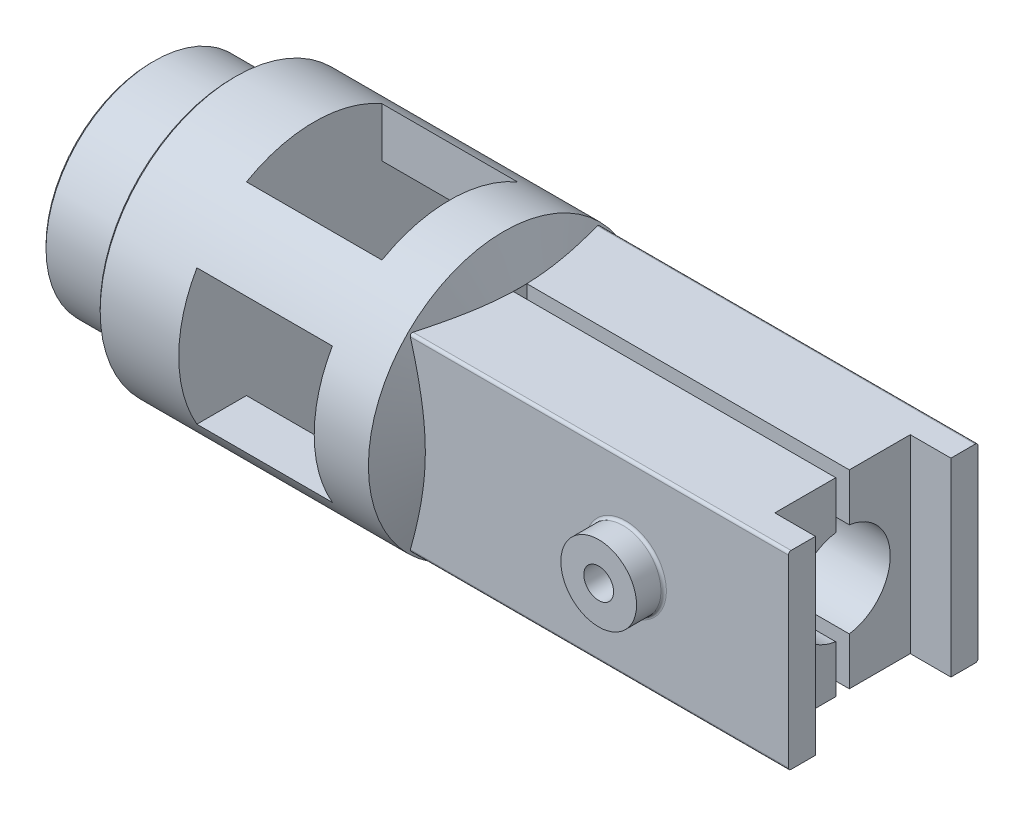
SolidWorks part; units mm, degrees
ref_plane "前视基准面" through (0, 0, 0) normal (0, 0, 1) x (1, 0, 0)
ref_plane "上视基准面" through (0, 0, 0) normal (0, 1, 0) x (1, 0, 0)
ref_plane "右视基准面" through (0, 0, 0) normal (1, 0, 0) x (0, 0, -1)
sketch "草图1" plane through (0, 0, 0) normal (0, 0, 1) x (1, 0, 0)
  line L0 (13, 0) -> (15, 0)
  line L1 (0, 0) -> (3, 0)
  line L2 (0, 0) -> (0, 4)
  line L3 (0, 4) -> (3, 4)
  line L4 (3, 0) -> (3, 4)
  line L5 (15, 0) -> (13, 5)
  line L6 (3, 0) -> (13, 0)
  line L7 (3, 0) -> (3, 5)
  line L8 (3, 5) -> (13, 5)
  line L9 (13, 0) -> (13, 5)
  point P8 (14.5028, 0)
  dimension "D1" = 4
  dimension "D2" = 5
  dimension "D3" = 3
  dimension "D4" = 13
  dimension "D5" = 15
revolve "旋转1" add sketch "草图1" angle 360 about L6
ref_plane "基准面1" through (6, 0, 0) normal (-1, 0, 0) x (0, 0, 1)
sketch "草图2" plane through (6, 0, 0) normal (-1, 0, 0) x (0, 0, 1)
  line L1 (-11.3913, 2.5) -> (11.3913, 2.5)
  line L2 (-11.3913, 2.5) -> (-11.3913, -2.5)
  line L3 (-11.3913, -2.5) -> (11.3913, -2.5)
  line L4 (11.3913, 2.5) -> (11.3913, -2.5)
  line L5 (-11.3913, 2.5) -> (11.3913, -2.5) construction
  line L6 (-11.3913, -2.5) -> (11.3913, 2.5) construction
  line L7 (-2.5, 14.208) -> (2.5, 14.208)
  line L8 (-2.5, 14.208) -> (-2.5, -14.208)
  line L9 (-2.5, -14.208) -> (2.5, -14.208)
  line L10 (2.5, 14.208) -> (2.5, -14.208)
  line L11 (-2.5, 14.208) -> (2.5, -14.208) construction
  line L12 (-2.5, -14.208) -> (2.5, 14.208) construction
  point P0 (0, 0)
  point P5 (0, 0)
  point P11 (-0.208, -1.7466)
  point P12 (0, 0)
  dimension "D1" = 5
extrude "切除-拉伸1" cut sketch "草图2" against normal blind 5 contours L1 L10 L3 L4 | L10 L3 L8 L9 | L10 L7 L8 L1 | L8 L1 L2 L3 | L10 L1 L8 L3
ref_plane "基准面2" through (27, 0, 0) normal (-1, 0, 0) x (0, 0, 1)
sketch "草图3" plane through (27, 0, 0) normal (-1, 0, 0) x (0, 0, 1)
  line L1 (-3.5, -3.5) -> (3.5, -3.5)
  line L2 (-3.5, -3.5) -> (-3.5, 3.5)
  line L3 (-3.5, 3.5) -> (3.5, 3.5)
  line L4 (3.5, -3.5) -> (3.5, 3.5)
  line L5 (-3.5, -3.5) -> (3.5, 3.5) construction
  line L6 (-3.5, 3.5) -> (3.5, -3.5) construction
  point P0 (0, 0)
  dimension "D1" = 7
extrude "凸台-拉伸1" add sketch "草图3" along normal up to next
sketch "草图4" plane through (27, 0, 0) normal (1, 0, 0) x (0, 0, -1)
  line L0 (-3.5, 3.5) -> (3.5, 3.5) construction
  line L1 (2.5, -3.5) -> (-2.5, -3.5)
  line L2 (2.5, -3.5) -> (2.5, 3.5)
  line L3 (2.5, 3.5) -> (-2.5, 3.5)
  line L4 (-2.5, -3.5) -> (-2.5, 3.5)
  line L5 (2.5, -3.5) -> (-2.5, 3.5) construction
  line L6 (2.5, 3.5) -> (-2.5, -3.5) construction
  point P0 (0, 0)
  dimension "D1" = 5
extrude "切除-拉伸2" cut sketch "草图4" against normal blind 1.5 contours L2 L1 L4 L3
sketch "草图5" plane through (25.5, 0, 0) normal (1, 0, 0) x (0, 0, -1)
  line L0 (2.5, -3.5) -> (-2.5, -3.5) construction
  line L1 (0.25, 3.5) -> (-0.25, 3.5)
  line L2 (0.25, 3.5) -> (0.25, -3.5)
  line L3 (0.25, -3.5) -> (-0.25, -3.5)
  line L4 (-0.25, 3.5) -> (-0.25, -3.5)
  line L5 (0.25, 3.5) -> (-0.25, -3.5) construction
  line L6 (0.25, -3.5) -> (-0.25, 3.5) construction
  circle A0 centre (0, 0) radius 1.7614
  dimension "4" = 3.5228
extrude "切除-拉伸3" cut sketch "草图5" against normal up to vertex (11.9 mm away) contours L4 A0 | L2 A0
sketch "草图6" plane through (0, 0, 3.5) normal (0, 0, 1) x (1, 0, 0)
  line L0 (27, -3.5) -> (27, 3.5) construction
  circle A0 centre (21, 0) radius 1.3966
  dimension "D1" = 6
extrude "凸台-拉伸2" add sketch "草图6" along normal blind 1
sketch "草图7" plane through (0, 0, 4.5) normal (0, 0, 1) x (1, 0, 0)
  circle A0 centre (21, 0) radius 0.55
  dimension "D1" = 1.1
extrude "切除-拉伸4" cut sketch "草图7" against normal through all
chamfer "倒角1" distance 0.5 angle 45 1 edges at (21.55, 0, -3.5)
fillet "圆角1" radius 0.1 1 edges at (19.6034, 0, 3.5)
chamfer "倒角2" distance 0.1 angle 45 2 edges at (3, 0, 5) (0, 0, 4)
fillet "圆角2" radius 0.1 4 edges at (20.0101, -3.5, -3.5) (20.0101, 3.5, -3.5) (20.0101, 3.5, 3.5) (20.0101, -3.5, 3.5)
sketch "草图8" plane through (0, 0, 0) normal (-1, 0, 0) x (0, 0, 1)
  circle A0 centre (0, 0) radius 2
extrude "切除-拉伸5" cut sketch "草图8" against normal blind 5 contours A0
cosmetic thread "装饰螺纹线1" parameters "D2"=5
chamfer "倒角3" distance 0.5 angle 45 1 edges at (0, 0, 2)
